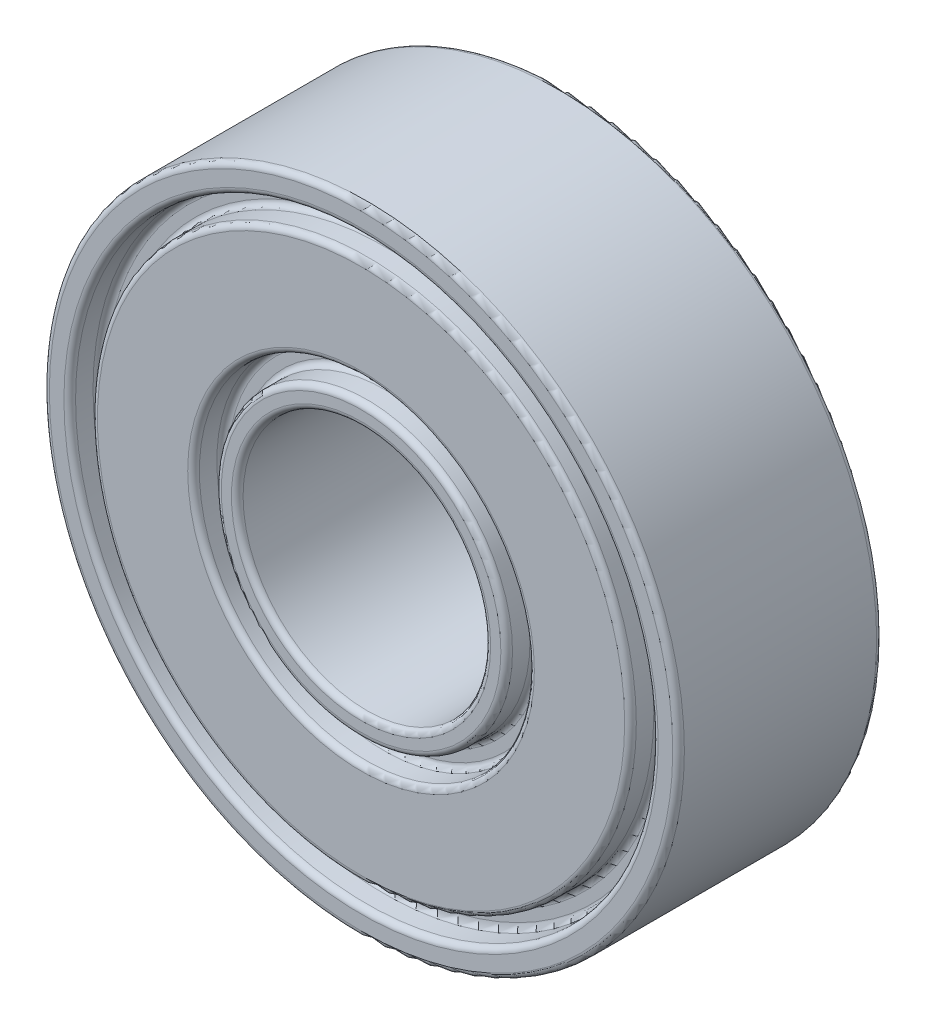
SolidWorks part; units mm, degrees
ref_plane "Front Plane" through (0, 0, 0) normal (0, 0, 1) x (1, 0, 0)
ref_plane "Top Plane" through (0, 0, 0) normal (0, 1, 0) x (1, 0, 0)
ref_plane "Right Plane" through (0, 0, 0) normal (1, 0, 0) x (0, 0, -1)
sketch "Sketch1" plane through (0, 0, 0) normal (0, 0, 1) x (1, 0, 0)
  circle A0 centre (0, 0) radius 10.9
  dimension "D1" = 21.8
extrude "Boss-Extrude1" add sketch "Sketch1" along normal blind 7
sketch "Sketch2" plane through (0, 0, 0) normal (0, 0, 1) x (1, 0, 0)
  circle A0 centre (0, 0) radius 4.25
  dimension "D1" = 8.5
extrude "Cut-Extrude1" cut sketch "Sketch2" along normal blind 7
sketch "Sketch3" plane through (0, 0, 0) normal (0, 0, 1) x (1, 0, 0)
  circle A0 centre (0, 0) radius 5
  circle A1 centre (0, 0) radius 5.75
  circle A2 centre (0, 0) radius 10
  circle A3 centre (0, 0) radius 9.25
  dimension "D1" = 20
  dimension "D2" = 18.5
  dimension "D3" = 10
  dimension "D4" = 11.5
extrude "Cut-Extrude2" cut sketch "Sketch3" along normal blind 1 contours A1 A0 | A2 A3
sketch "Sketch4" plane through (0, 0, 0) normal (0, 0, 1) x (1, 0, 0)
  circle A0 centre (0, 0) radius 5
  circle A1 centre (0, 0) radius 5.75
  circle A2 centre (0, 0) radius 9.25
  circle A3 centre (0, 0) radius 10
  dimension "D1" = 20
  dimension "D2" = 18.5
  dimension "D3" = 10
  dimension "D4" = 11.5
extrude "Cut-Extrude3" cut sketch "Sketch4" against normal blind 1 from surface at 7 contours A3 A2 | A1 A0 starting at face at (4.25, 0, 7)
fillet "Fillet1" radius 0.2 20 edges at (5.75, 0, 1) (5, 0, 1) (10, 0, 1) (9.25, 0, 1) (5.75, 0, 6) (5, 0, 6) (10, 0, 6) (9.25, 0, 6) (10.9, 0, 0) (10, 0, 0) (9.25, 0, 0) (5.75, 0, 0) (5, 0, 0) (4.25, 0, 0) (5, 0, 7) (4.25, 0, 7) (10.9, 0, 7) (10, 0, 7) (9.25, 0, 7) (5.75, 0, 7)
